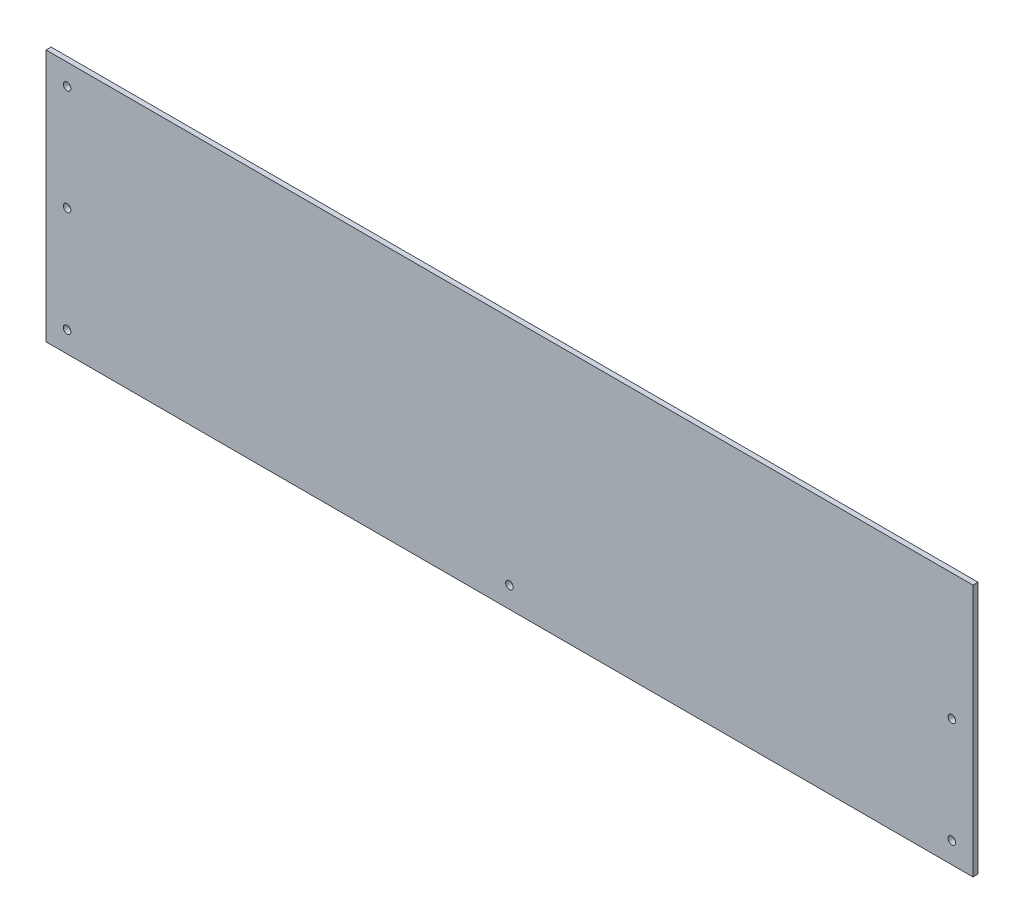
SolidWorks part; units mm, degrees
material "Acrylic (Medium-high impact)"
ref_plane "Front Plane" through (0, 0, 0) normal (0, 0, 1) x (1, 0, 0)
ref_plane "Top Plane" through (0, 0, 0) normal (0, 1, 0) x (1, 0, 0)
ref_plane "Right Plane" through (0, 0, 0) normal (1, 0, 0) x (0, 0, -1)
sketch "Sketch1" plane through (0, 0, 0) normal (0, 0, 1) x (1, 0, 0)
  line L0 (550, 0) -> (550, 150) construction
  line L1 (0, 0) -> (550, 0)
  line L2 (0, 0) -> (0, 150)
  line L3 (0, 150) -> (550, 150)
  line L4 (550, 0) -> (550, 150)
  line L6 (23.0371, 150) -> (16.82, 150) construction
extrude "Boss-Extrude1" add sketch "Sketch1" along normal blind 3
hole_wizard "M4 Clearance Hole1" positions "Sketch2" profile "Sketch3" hole size "M4" standard "ANSI Metric" end condition through all
sketch "Sketch2" plane through (0, 0, 3) normal (0, 0, 1) x (1, 0, 0)
  line L1 (550, 150) -> (0, 150) construction
  line L2 (0, 150) -> (0, 0) construction
  line L3 (0, 0) -> (550, 0) construction
  line L4 (550, 0) -> (550, 150) construction
  point P0 (12.5, 75)
  point P2 (12.5, 137.5)
  point P4 (12.5, 12.5)
  point P6 (275, 12.5)
  point P10 (537.5, 12.5)
  point P12 (537.5, 75)
  point P14 (537.5, 237.5)
  point P40 (0, 75)
  point P42 (275, 0)
  dimension "D1" = 12.5
  dimension "D2" = 12.5
  dimension "D3" = 12.5
  dimension "D4" = 12.5
sketch "Sketch3" plane through (12.5, 75, 3) normal (1, 0, 0) x (0, -1, 0)
  line L0 (0, 0) -> (0, 3)
  line L1 (0, 3) -> (2.25, 3)
  line L2 (2.25, 3) -> (2.25, 0)
  line L5 (2.25, 0) -> (0, 0)
  line L11 (0, -6.35) -> (0, 107.95) construction
  dimension "Thru Hole Dia." = 4.5
  dimension "Thru Hole Depth" = 3
